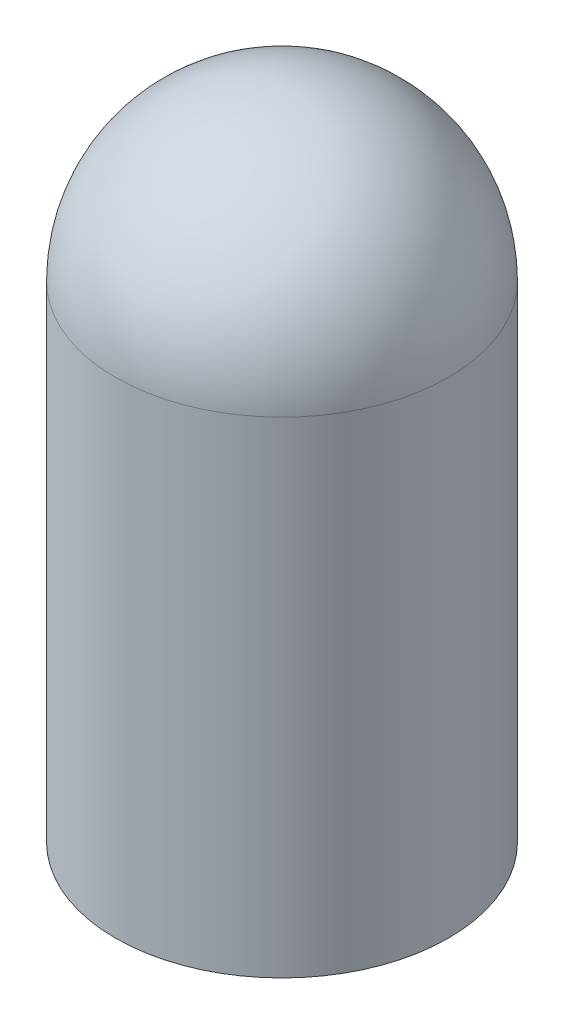
SolidWorks part; units mm, degrees
ref_plane "Front Plane" through (0, 0, 0) normal (0, 0, 1) x (1, 0, 0)
ref_plane "Top Plane" through (0, 0, 0) normal (0, 1, 0) x (1, 0, 0)
ref_plane "Right Plane" through (0, 0, 0) normal (1, 0, 0) x (0, 0, -1)
sketch "Sketch1" plane through (0, 0, 0) normal (0, 0, 1) x (1, 0, 0)
  line L0 (12, 0) -> (12, -35)
  line L1 (10.5, 0) -> (10.5, -35)
  line L2 (10.5, -35) -> (12, -35)
  line L3 (0, 12) -> (0, 10.5)
  line L4 (0, 12) -> (0, -35) construction
  arc A0 (12, 0) -> (0, 12) centre (0, 0) ccw
  arc A1 (10.5, 0) -> (0, 10.5) centre (0, 0) ccw
  dimension "D1" = 21
  dimension "D2" = 24
  dimension "D3" = 35
revolve "Revolve1" add sketch "Sketch1" angle 360 about L4
